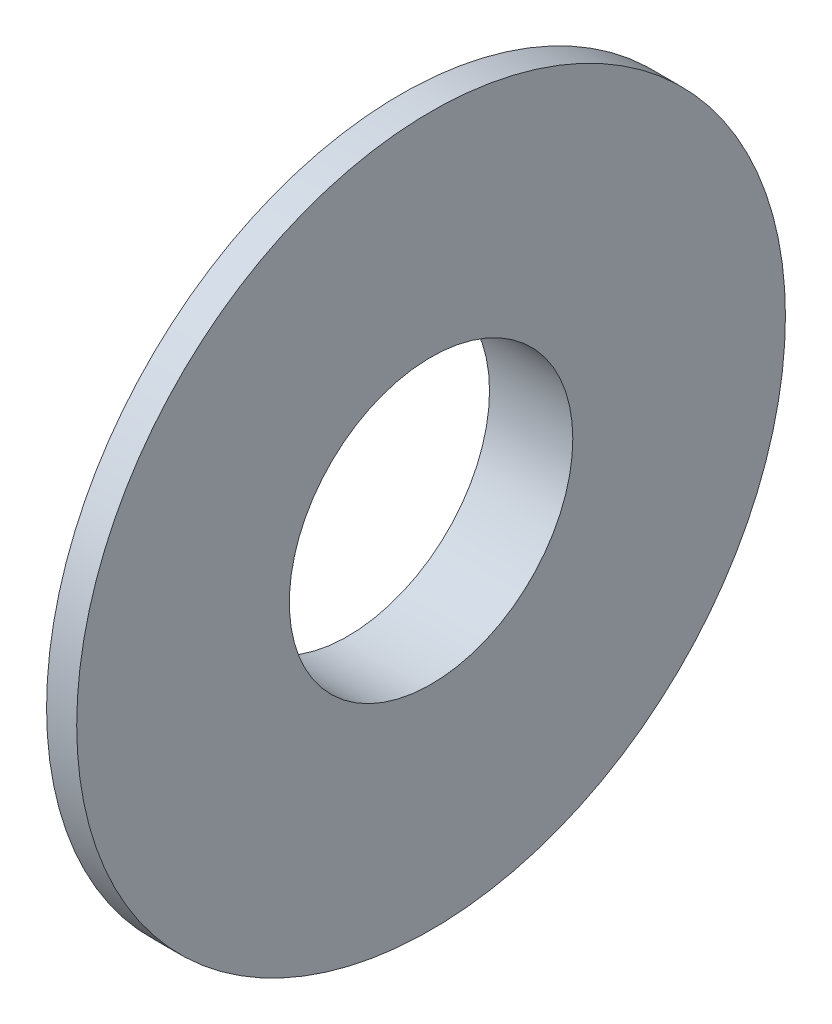
SolidWorks part; units mm, degrees
ref_plane "Front Plane" through (0, 0, 0) normal (0, 0, 1) x (1, 0, 0)
ref_plane "Top Plane" through (0, 0, 0) normal (0, 1, 0) x (1, 0, 0)
ref_plane "Right Plane" through (0, 0, 0) normal (1, 0, 0) x (0, 0, -1)
sketch "Sketch1" plane through (0, 0, 0) normal (0, 0, 1) x (1, 0, 0)
  line L0 (-1.5, 4) -> (-1.5, 5.5)
  line L1 (55, 0) -> (-55, 0) construction
  line L2 (-1.5, 5.5) -> (0, 5.5)
  line L3 (0, 5.5) -> (0, 10)
  line L4 (0, 10) -> (0.85, 10)
  line L5 (0.85, 10) -> (0.85, 4)
  line L6 (27.8934, 0) -> (-12.2596, 0)
  line L7 (-1.5, 4) -> (0.85, 4)
  line L8 (0, -55) -> (0, 55) construction
  dimension "D1" = 0.85
  dimension "D2" = 4
  dimension "D3" = 10
  dimension "D4" = 1.5
  dimension "D5" = 5.5
ref_axis "Axis1" through (-14.2672, 0, 0) along (1, 0, 0)
revolve "Revolve1" add sketch "Sketch1" angle 360 about axis through (-14.2672, 0, 0) along (1, 0, 0)
